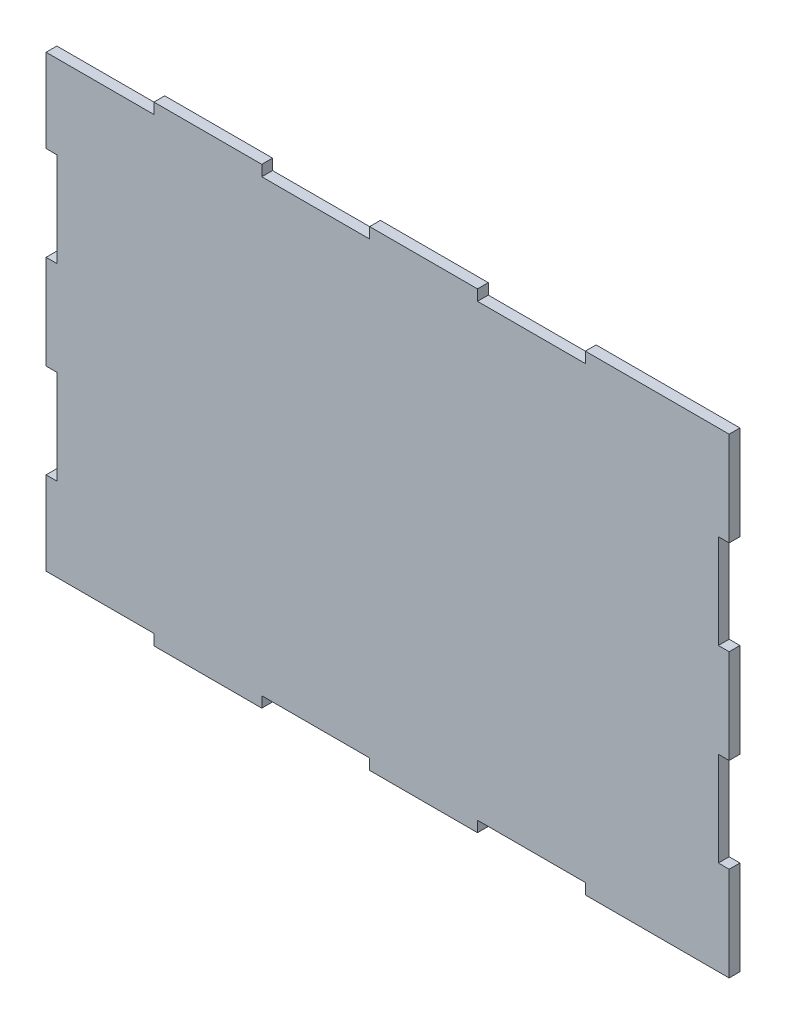
SolidWorks part; units mm, degrees
material "Acrylic (Medium-high impact)"
ref_plane "Front Plane" through (0, 0, 0) normal (0, 0, 1) x (1, 0, 0)
ref_plane "Top Plane" through (0, 0, 0) normal (0, 1, 0) x (1, 0, 0)
ref_plane "Right Plane" through (0, 0, 0) normal (1, 0, 0) x (0, 0, -1)
sketch "Sketch1" plane through (0, 0, 0) normal (0, 0, 1) x (1, 0, 0)
  line L254 (60, 131) -> (90, 131)
  line L255 (0, 0) -> (190, 0)
  line L256 (0, 0) -> (0, 131)
  line L257 (0, 131) -> (190, 131)
  line L258 (190, 0) -> (190, 131)
  line L259 (0, 131) -> (30, 131)
  line L260 (0, 131) -> (0, 128)
  line L261 (0, 128) -> (30, 128)
  line L262 (30, 131) -> (30, 128)
  line L263 (60, 131) -> (60, 128)
  line L264 (60, 128) -> (90, 128)
  line L265 (90, 131) -> (90, 128)
  line L266 (120, 131) -> (150, 131)
  line L267 (120, 131) -> (120, 128)
  line L268 (120, 128) -> (150, 128)
  line L269 (150, 131) -> (150, 128)
  line L270 (60, 3) -> (90, 3)
  line L271 (60, 3) -> (60, 0)
  line L272 (60, 0) -> (90, 0)
  line L273 (90, 3) -> (90, 0)
  line L274 (120, 3) -> (150, 3)
  line L275 (120, 3) -> (120, 0)
  line L276 (120, 0) -> (150, 0)
  line L277 (150, 3) -> (150, 0)
  line L278 (0, 3) -> (30, 3)
  line L279 (0, 3) -> (0, 0)
  line L280 (0, 0) -> (30, 0)
  line L281 (30, 3) -> (30, 0)
  line L282 (187, 104.8) -> (187, 78.6)
  line L283 (0, 104.8) -> (3, 104.8)
  line L284 (0, 104.8) -> (0, 78.6)
  line L285 (0, 78.6) -> (3, 78.6)
  line L286 (3, 104.8) -> (3, 78.6)
  line L287 (187, 104.8) -> (190, 104.8)
  line L288 (190, 104.8) -> (190, 78.6)
  line L289 (187, 78.6) -> (190, 78.6)
  line L290 (187, 52.4) -> (187, 26.2)
  line L291 (187, 52.4) -> (190, 52.4)
  line L292 (190, 52.4) -> (190, 26.2)
  line L293 (187, 26.2) -> (190, 26.2)
  line L294 (0, 52.4) -> (0, 26.2)
  line L295 (0, 52.4) -> (3, 52.4)
  line L296 (3, 52.4) -> (3, 26.2)
  line L297 (0, 26.2) -> (3, 26.2)
  dimension "D1" = 190
  dimension "D2" = 131
  dimension "D3" = 3
  dimension "D4" = 30
  dimension "D7" = 26.2
  dimension "D8" = 2
  dimension "D5" = 3
  dimension "D6" = 26.2
  dimension "D9" = 2
extrude "Boss-Extrude1" add sketch "Sketch1" along normal blind 3 contours L297 L256 L278 L281 L255 L271 L270 L273 L275 L274 L277 L258 L293 L290 L291 L289 L282 L287 L257 L269 L268 L267 L265 L264 L263 L262 L261 L283 L286 L285 L295 L296
